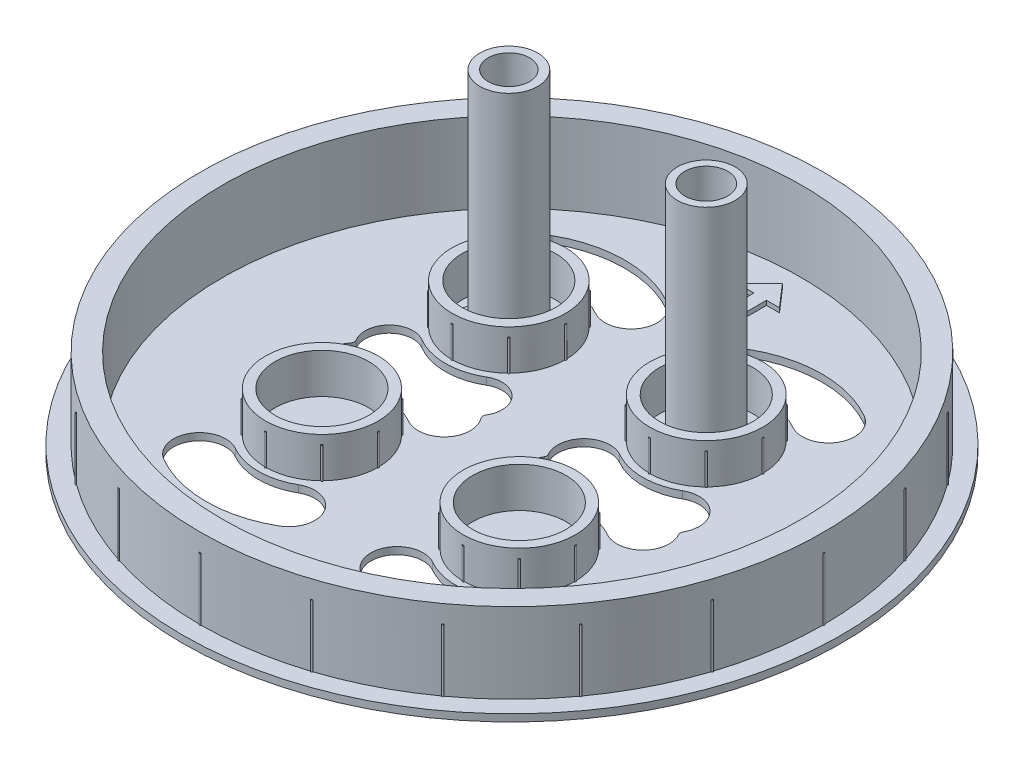
SolidWorks part; units mm, degrees
ref_plane "Front Plane" through (0, 0, 0) normal (0, 0, 1) x (1, 0, 0)
ref_plane "Top Plane" through (0, 0, 0) normal (0, 1, 0) x (1, 0, 0)
ref_plane "Right Plane" through (0, 0, 0) normal (1, 0, 0) x (0, 0, -1)
sketch "Sketch1" plane through (0, 0, 0) normal (0, 1, 0) x (1, 0, 0)
  circle A0 centre (0, 0) radius 74
  dimension "D1" = 148
extrude "Boss-Extrude1" add sketch "Sketch1" along normal blind 1.6
sketch "Sketch2" plane through (0, 1.6, 0) normal (0, 1, 0) x (1, 0, 0)
  circle A0 centre (0, 0) radius 70
  dimension "D1" = 140
extrude "Boss-Extrude2" add sketch "Sketch2" along normal blind 18
sketch "Sketch3" plane through (0, 19.6, 0) normal (0, 1, 0) x (1, 0, 0)
  circle A0 centre (0, 0) radius 65
  dimension "D1" = 130
extrude "Cut-Extrude1" cut sketch "Sketch3" against normal blind 18
sketch "Sketch4" plane through (0, 1.6, 0) normal (0, 1, 0) x (1, 0, 0)
  circle A0 centre (0, 70) radius 0.2
  circle A1 centre (0, 0) radius 70 construction
  circle A2 centre (21.6312, 66.574) radius 0.2
  circle A3 centre (41.145, 56.6312) radius 0.2
  circle A4 centre (56.6312, 41.145) radius 0.2
  circle A5 centre (66.574, 21.6312) radius 0.2
  circle A6 centre (70, 0) radius 0.2
  circle A7 centre (66.574, -21.6312) radius 0.2
  circle A8 centre (56.6312, -41.145) radius 0.2
  circle A9 centre (41.145, -56.6312) radius 0.2
  circle A10 centre (21.6312, -66.574) radius 0.2
  circle A11 centre (0, -70) radius 0.2
  circle A12 centre (-21.6312, -66.574) radius 0.2
  circle A13 centre (-41.145, -56.6312) radius 0.2
  circle A14 centre (-56.6312, -41.145) radius 0.2
  circle A15 centre (-66.574, -21.6312) radius 0.2
  circle A16 centre (-70, 0) radius 0.2
  circle A17 centre (-66.574, 21.6312) radius 0.2
  circle A18 centre (-56.6312, 41.145) radius 0.2
  circle A19 centre (-41.145, 56.6312) radius 0.2
  circle A20 centre (-21.6312, 66.574) radius 0.2
  point P46 (0, 0)
  dimension "D1" = 0.4
  dimension "D2" = 20
extrude "Boss-Extrude3" add sketch "Sketch4" along normal blind 14
sketch "Sketch5" plane through (0, 1.6, 0) normal (0, 1, 0) x (1, 0, 0)
  circle A0 centre (-23.2709, 22.5783) radius 12.75
  circle A2 centre (21.0546, 22.5783) radius 12.7
  circle A4 centre (-23.2709, -19.3924) radius 12.65
  circle A6 centre (21.0546, -19.3924) radius 12.6
  point P3 (-24.379, 27.1494)
  point P4 (0, 0)
  point P5 (-25.6257, 26.3183)
  point P9 (21.0546, 26.3183)
  point P10 (-23.2709, 26.3183)
  point P17 (-23.2709, -15.791)
  point P18 (21.0546, -15.791)
  point P19 (0, 0)
  point P20 (-23.2709, -19.3924)
  point P21 (21.0546, -19.3924)
  point P22 (21.0546, 22.5783)
  point P23 (-23.2709, 22.5783)
  dimension "D1" = 25.5
  dimension "D3" = 25.4
  dimension "D5" = 25.3
  dimension "D6" = 25.2
extrude "Boss-Extrude4" add sketch "Sketch5" along normal blind 9
sketch "Sketch6" plane through (0, 10.6, 0) normal (0, 1, 0) x (1, 0, 0)
  circle A0 centre (-23.2709, 22.5783) radius 10.5
  circle A1 centre (21.0546, 22.5783) radius 10.5
  circle A2 centre (21.0546, -19.3924) radius 10.5
  circle A3 centre (-23.2709, -19.3924) radius 10.5
  dimension "D1" = 21
  dimension "D2" = 21
  dimension "D3" = 21
  dimension "D4" = 21
extrude "Cut-Extrude2" cut sketch "Sketch6" against normal blind 9
sketch "Sketch7" plane through (0, 1.6, 0) normal (0, 1, 0) x (1, 0, 0)
  circle A0 centre (-23.2709, 35.3283) radius 0.2
  circle A1 centre (-23.2709, 22.5783) radius 12.75 construction
  circle A2 centre (-23.2709, 22.5783) radius 12.75 construction
  circle A3 centre (-14.2553, 31.5939) radius 0.2
  circle A4 centre (-10.5209, 22.5783) radius 0.2
  circle A5 centre (-14.2553, 13.5627) radius 0.2
  circle A6 centre (-23.2709, 9.8283) radius 0.2
  circle A7 centre (-32.2865, 13.5627) radius 0.2
  circle A8 centre (-36.0209, 22.5783) radius 0.2
  circle A9 centre (-32.2865, 31.5939) radius 0.2
  circle A10 centre (21.0546, 35.2783) radius 0.2
  circle A11 centre (21.0546, 22.5783) radius 12.7 construction
  circle A12 centre (21.0546, 22.5783) radius 12.7 construction
  circle A13 centre (-23.2709, -6.7424) radius 0.2
  circle A14 centre (-23.2709, -19.3924) radius 12.65 construction
  circle A15 centre (-23.2709, -19.3924) radius 12.65 construction
  circle A16 centre (21.0546, -6.7924) radius 0.2
  circle A17 centre (21.0546, -19.3924) radius 12.6 construction
  circle A18 centre (30.0349, 31.5586) radius 0.2
  circle A19 centre (33.7546, 22.5783) radius 0.2
  circle A20 centre (30.0349, 13.598) radius 0.2
  circle A21 centre (21.0546, 9.8783) radius 0.2
  circle A22 centre (12.0744, 13.598) radius 0.2
  circle A23 centre (8.3546, 22.5783) radius 0.2
  circle A24 centre (12.0744, 31.5586) radius 0.2
  circle A25 centre (-14.326, -10.4475) radius 0.2
  circle A26 centre (-10.6209, -19.3924) radius 0.2
  circle A27 centre (-14.326, -28.3373) radius 0.2
  circle A28 centre (-23.2709, -32.0424) radius 0.2
  circle A29 centre (-32.2158, -28.3373) radius 0.2
  circle A30 centre (-35.9209, -19.3924) radius 0.2
  circle A31 centre (-32.2158, -10.4475) radius 0.2
  circle A32 centre (29.9642, -10.4829) radius 0.2
  circle A33 centre (33.6546, -19.3924) radius 0.2
  circle A34 centre (29.9642, -28.3019) radius 0.2
  circle A35 centre (21.0546, -31.9924) radius 0.2
  circle A36 centre (12.1451, -28.3019) radius 0.2
  circle A37 centre (8.4546, -19.3924) radius 0.2
  circle A38 centre (12.1451, -10.4829) radius 0.2
  point P23 (-23.2709, 22.5783)
  point P54 (21.0546, 22.5783)
  point P69 (-23.2709, -19.3924)
  point P84 (21.0546, -19.3924)
  dimension "D1" = 0.4
  dimension "D3" = 0.4
  dimension "D4" = 0.4
  dimension "D5" = 0.4
  dimension "D2" = 8
  dimension "D6" = 8
  dimension "D7" = 8
  dimension "D8" = 8
extrude "Boss-Extrude5" add sketch "Sketch7" along normal blind 7
sketch "Sketch8" plane through (0, 1.6, 0) normal (0, 1, 0) x (1, 0, 0)
  arc A0 (-13.2709, 40.043) -> (-33.2709, 40.043) centre (-23.2709, 22.5783) ccw construction
  arc A1 (-10.3516, 45.1414) -> (-36.1901, 45.1414) centre (-23.2709, 22.5783) ccw
  arc A2 (-16.1901, 34.9446) -> (-30.3516, 34.9446) centre (-23.2709, 22.5783) ccw
  arc A3 (-16.1901, 34.9446) -> (-10.3516, 45.1414) centre (-13.2709, 40.043) ccw
  arc A4 (-36.1901, 45.1414) -> (-30.3516, 34.9446) centre (-33.2709, 40.043) ccw
  arc A5 (31.0546, 40.043) -> (11.0546, 40.043) centre (21.0546, 22.5783) ccw construction
  arc A6 (33.9739, 45.1414) -> (8.1354, 45.1414) centre (21.0546, 22.5783) ccw
  arc A7 (28.1354, 34.9446) -> (13.9739, 34.9446) centre (21.0546, 22.5783) ccw
  arc A8 (28.1354, 34.9446) -> (33.9739, 45.1414) centre (31.0546, 40.043) ccw
  arc A9 (8.1354, 45.1414) -> (13.9739, 34.9446) centre (11.0546, 40.043) ccw
  arc A10 (36.1742, 1.2506) -> (36.1742, 2.2316) centre (37.0456, 1.7411) cw
  arc A12 (-16.1901, -7.0261) -> (-30.3516, -7.0261) centre (-23.2709, -19.3924) ccw
  arc A13 (-16.1901, -7.0261) -> (-8.645, 1.6941) centre (-13.2709, -1.9277) ccw
  arc A14 (-37.8967, 1.6941) -> (-30.3516, -7.0261) centre (-33.2709, -1.9277) ccw
  arc A15 (31.0546, -1.6314) -> (30.8397, -1.5101) centre (21.0546, -19.0961) ccw construction
  arc A17 (28.1354, -6.7298) -> (13.9739, -6.7298) centre (21.0546, -19.0961) ccw
  arc A18 (28.1354, -6.7298) -> (36.1742, 1.2506) centre (31.0546, -1.6314) ccw
  arc A19 (5.935, 1.2506) -> (13.9739, -6.7298) centre (11.0546, -1.6314) ccw
  arc A20 (11.0546, -36.8571) -> (31.0546, -36.8571) centre (21.0546, -19.3924) ccw construction
  arc A21 (8.1354, -41.9555) -> (33.9739, -41.9555) centre (21.0546, -19.3924) ccw
  arc A22 (13.9739, -31.7587) -> (28.1354, -31.7587) centre (21.0546, -19.3924) ccw
  arc A23 (13.9739, -31.7587) -> (8.1354, -41.9555) centre (11.0546, -36.8571) ccw
  arc A24 (33.9739, -41.9555) -> (28.1354, -31.7587) centre (31.0546, -36.8571) ccw
  arc A25 (-33.2709, -36.8571) -> (-13.2709, -36.8571) centre (-23.2709, -19.3924) ccw construction
  arc A26 (-36.1901, -41.9555) -> (-10.3516, -41.9555) centre (-23.2709, -19.3924) ccw
  arc A27 (-30.3516, -31.7587) -> (-16.1901, -31.7587) centre (-23.2709, -19.3924) ccw
  arc A28 (-30.3516, -31.7587) -> (-36.1901, -41.9555) centre (-33.2709, -36.8571) ccw
  arc A29 (-10.3516, -41.9555) -> (-16.1901, -31.7587) centre (-13.2709, -36.8571) ccw
  arc A30 (5.935, 2.2316) -> (5.935, 1.2506) centre (5.0636, 1.7411) cw
  arc A32 (13.9739, 10.212) -> (28.1354, 10.212) centre (21.0546, 22.5783) ccw
  arc A33 (13.9739, 10.212) -> (5.935, 2.2316) centre (11.0546, 5.1136) ccw
  arc A34 (36.1742, 2.2316) -> (28.1354, 10.212) centre (31.0546, 5.1136) ccw
  arc A35 (11.2695, -1.5101) -> (11.0546, -1.6314) centre (21.0546, -19.0961) ccw construction
  arc A37 (-30.5303, 10.316) -> (-16.0115, 10.316) centre (-23.2709, 22.5783) ccw
  arc A38 (-30.5303, 10.316) -> (-37.8356, 2.8397) centre (-33.2709, 5.6867) ccw
  arc A39 (-8.7062, 2.8397) -> (-16.0115, 10.316) centre (-13.2709, 5.6867) ccw
  arc A40 (-8.645, 1.6941) -> (-8.7062, 2.8397) centre (-7.8577, 2.3105) cw
  arc A41 (-37.8967, 1.6941) -> (-37.8356, 2.8397) centre (-38.6841, 2.3105) ccw
  point P4 (-23.2709, 42.7033)
  point P9 (-24.2837, 42.408)
  point P10 (-32.1065, 39.9757)
  point P11 (-14.16, 39.1211)
  point P15 (21.0546, 42.7033)
  point P20 (21.0546, 22.5783)
  point P25 (-23.2709, 0.7326)
  point P30 (0, 0)
  point P34 (21.0546, 1.0289)
  point P39 (-23.2709, -19.3111)
  point P40 (21.0546, -19.3111)
  point P41 (-25.3634, -19.3111)
  point P42 (-23.2709, -19.3924)
  point P44 (0, 0)
  point P48 (21.0546, -39.5174)
  point P53 (-13.6871, 3.8656)
  point P54 (0, 18.8273)
  point P55 (21.0546, -19.3924)
  point P60 (-23.2709, -39.5174)
  point P68 (21.0546, 2.4533)
  point P76 (-23.2709, 2.9485)
  point P81 (21.0546, 22.5783)
  point P82 (-23.2709, 22.5783)
  point P83 (-23.2709, -19.3924)
  dimension "D1" = 14.25
  dimension "D2" = 26
  dimension "D3" = 14.25
  dimension "D4" = 14.25
  dimension "D5" = 14.25
  dimension "D6" = 14.25
  dimension "D7" = 14.25
  dimension "D8" = 14.25
  dimension "D9" = 14.25
  dimension "D10" = 26
  dimension "D11" = 1
  dimension "D14" = 26
  dimension "D15" = 26
  dimension "D16" = 20
  dimension "D17" = 20
extrude "Cut-Extrude4" cut sketch "Sketch8" against normal through all
sketch "Sketch9" plane through (0, 1.6, 0) normal (0, 1, 0) x (1, 0, 0)
  circle A0 centre (-23.2709, 22.5783) radius 6.5
  circle A1 centre (21.0546, 22.5783) radius 6.5
  dimension "D1" = 13
  dimension "D2" = 13
extrude "Boss-Extrude6" add sketch "Sketch9" along normal blind 50
sketch "Sketch12" plane through (0, 1.6, 0) normal (0, 1, 0) x (1, 0, 0)
  line L0 (0, 60.7382) -> (-5.0677, 55.6705)
  line L1 (-5.0677, 55.6705) -> (-1.3355, 55.6705)
  line L2 (-1.3355, 55.6705) -> (-1.3355, 50.4455)
  line L3 (-1.3355, 50.4455) -> (1.4931, 50.4455)
  line L4 (1.4931, 50.4455) -> (1.4931, 55.6705)
  line L5 (1.4931, 55.6705) -> (4.4001, 55.6705)
  line L6 (4.4001, 55.6705) -> (0, 60.7382)
  line L7 (-28.4831, 29.4647) -> (-31.8913, 17.3689)
  line L8 (-31.8913, 17.3689) -> (-14.9328, 17.3689)
  line L9 (-14.9328, 17.3689) -> (-18.0882, 29.4647)
  line L10 (-18.0882, 29.4647) -> (-28.4831, 29.4647)
  line L12 (14.3863, 29.3332) -> (27.6654, 29.3332)
  line L13 (14.3863, 29.3332) -> (14.3863, 15.9884)
  line L14 (14.3863, 15.9884) -> (27.6654, 15.9884)
  line L15 (27.6654, 29.3332) -> (27.6654, 15.9884)
  point P9 (14.3863, 29.3332)
extrude "Boss-Extrude7" add sketch "Sketch12" along normal blind 1
sketch "Sketch14" plane through (0, 0, 0) normal (0, -1, 0) x (1, 0, 0)
  circle A0 centre (21.0546, -22.5783) radius 4.825
  dimension "D1" = 9.65
extrude "Cut-Extrude5" cut sketch "Sketch14" against normal through all
sketch "Sketch15" plane through (0, 0, 0) normal (0, -1, 0) x (1, 0, 0)
  circle A0 centre (-23.2709, -22.5783) radius 4.825
  dimension "D1" = 9.65
extrude "Cut-Extrude6" cut sketch "Sketch15" against normal up to next (51.6 mm away) draft 0.2
